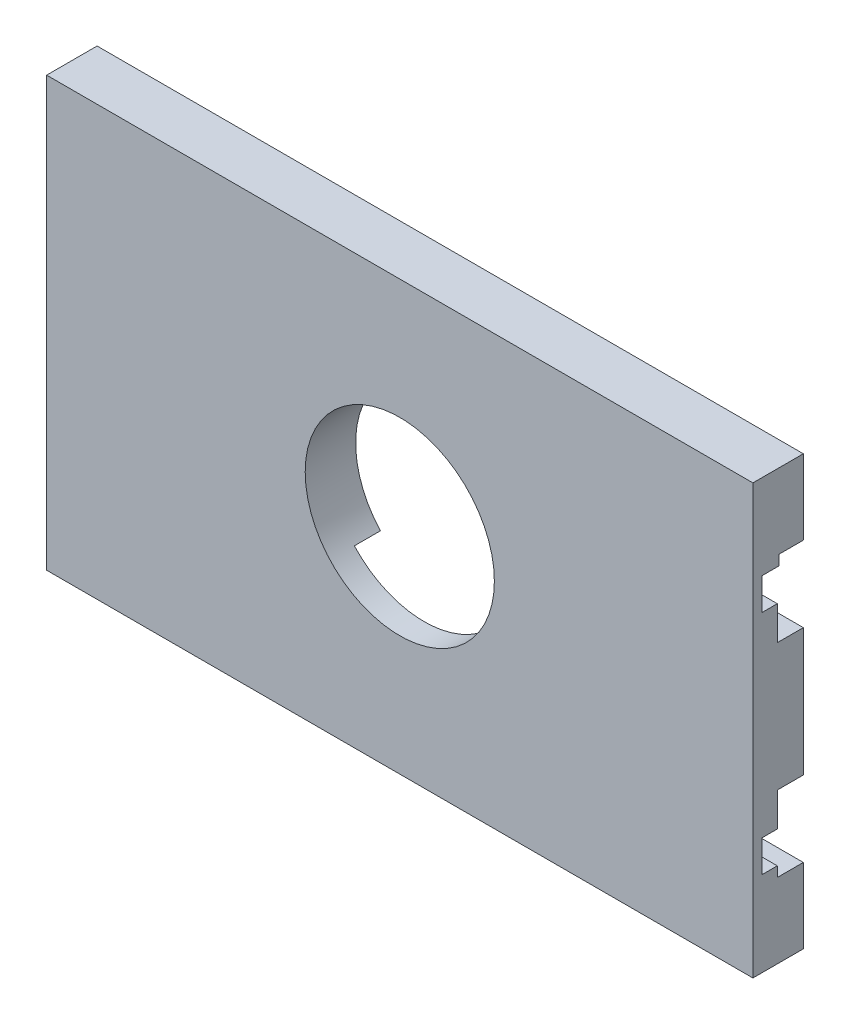
SolidWorks part; units mm, degrees
ref_plane "Front Plane" through (0, 0, 0) normal (0, 0, 1) x (1, 0, 0)
ref_plane "Top Plane" through (0, 0, 0) normal (0, 1, 0) x (1, 0, 0)
ref_plane "Right Plane" through (0, 0, 0) normal (1, 0, 0) x (0, 0, -1)
sketch "Sketch1" plane through (0, 0, 0) normal (1, 0, 0) x (0, 0, -1)
  line L0 (5, 27.66) -> (0.16, 27.66)
  line L1 (-5, -42.5) -> (5, -42.5)
  line L2 (-5, -42.5) -> (-5, 42.5)
  line L3 (-5, 42.5) -> (5, 42.5)
  line L4 (5, -42.5) -> (5, 42.5)
  line L5 (-5, -42.5) -> (5, 42.5) construction
  line L6 (-5, 42.5) -> (5, -42.5) construction
  line L7 (0.16, 27.66) -> (0.16, 25.66)
  line L8 (0.16, 25.66) -> (-3.16, 25.66)
  line L9 (-3.16, 25.66) -> (-3.16, 19.34)
  line L12 (-3.16, 19.34) -> (-0.16, 19.34)
  line L13 (-0.16, 19.34) -> (-0.16, 12.6506)
  line L14 (-0.16, 12.6506) -> (5, 12.6506)
  line L16 (5, 12.6506) -> (5, 27.66)
  line L17 (5, -27.66) -> (-0.16, -27.66)
  line L18 (-0.16, -27.66) -> (-0.16, -25.66)
  line L19 (-0.16, -25.66) -> (-3.16, -25.66)
  line L20 (-3.16, -19.34) -> (-3.16, -25.66)
  line L21 (-3.16, -19.34) -> (-0.16, -19.34)
  line L22 (-0.16, -19.34) -> (-0.16, -12.6506)
  line L23 (-0.16, -12.6506) -> (5, -12.6506)
  point P0 (0, 0)
  point P42 (2.42, -27.66)
  dimension "D1" = 85
  dimension "D2" = 10
  dimension "D3" = 5.16
  dimension "D4" = 2
  dimension "D5" = 3
  dimension "D6" = 6.32
  dimension "D7" = 3
  dimension "D8" = 6.6894
  dimension "D9" = 5.16
  dimension "D10" = 14.84
  dimension "D11" = 8.16
  dimension "D12" = 5.16
  dimension "D13" = 6.6894
  dimension "D14" = 6.32
  dimension "D15" = 2
  dimension "D16" = 4.84
  dimension "D17" = 14.84
  dimension "D18" = 8.16
  dimension "D19" = 3.32
  dimension "D20" = 3
extrude "Boss-Extrude1" add sketch "Sketch1" along normal blind 140 contours L22 L23 L4 L14 L13 L12 L9 L8 L7 L0 L3 L2 L1 L17 L18 L19 L20 L21
sketch "Sketch2" plane through (0, 0, 5) normal (0, 0, 1) x (1, 0, 0)
  line L0 (140, -42.5) -> (140, 42.5) construction
  line L1 (140, -42.5) -> (0, -42.5) construction
  circle A0 centre (70, 0) radius 18.75
  point P6 (40.0506, -40.0559)
  dimension "D1" = 37.5
  dimension "D2" = 70
  dimension "D3" = 42.5
extrude "Cut-Extrude1" cut sketch "Sketch2" against normal through all
